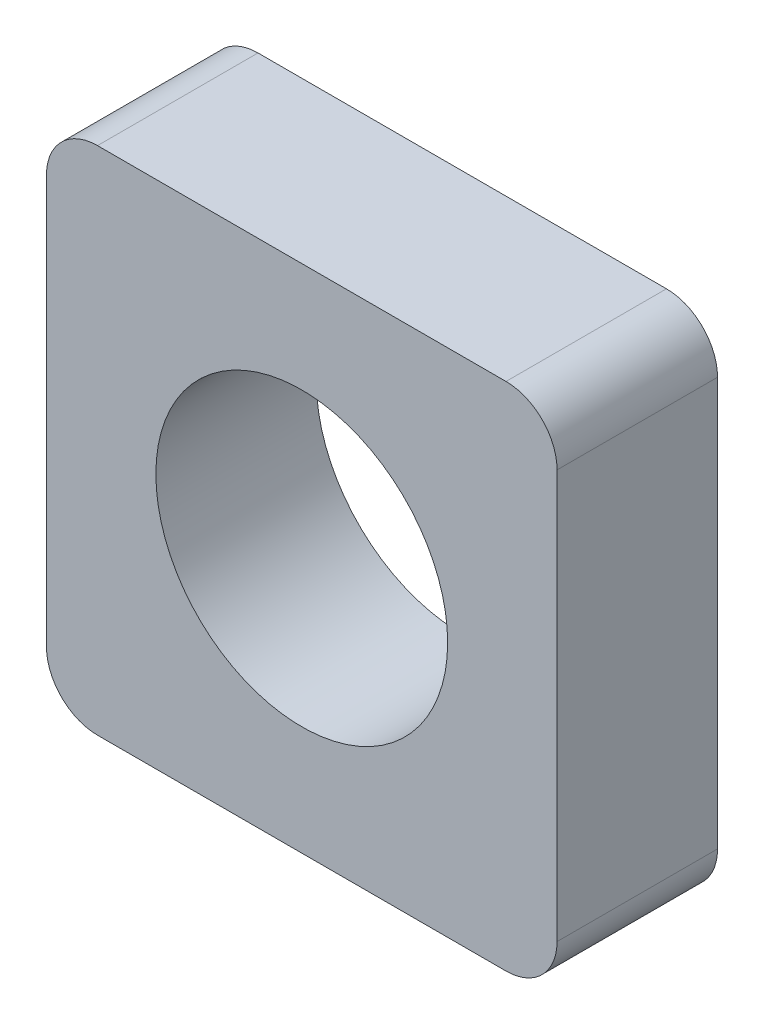
SolidWorks part; units mm, degrees
material "Cast Stainless Steel"
ref_plane "Front Plane" through (0, 0, 0) normal (0, 0, 1) x (1, 0, 0)
ref_plane "Top Plane" through (0, 0, 0) normal (0, 1, 0) x (1, 0, 0)
ref_plane "Right Plane" through (0, 0, 0) normal (1, 0, 0) x (0, 0, -1)
sketch "Sketch1" plane through (0, 0, 0) normal (0, 0, 1) x (1, 0, 0)
  line L1 (-3.5, 3.5) -> (3.5, 3.5)
  line L2 (-3.5, 3.5) -> (-3.5, -3.5)
  line L3 (-3.5, -3.5) -> (3.5, -3.5)
  line L4 (3.5, 3.5) -> (3.5, -3.5)
  line L5 (-3.5, 3.5) -> (3.5, -3.5) construction
  line L6 (-3.5, -3.5) -> (3.5, 3.5) construction
  circle A0 centre (0, 0) radius 2
  dimension "D2" = 4
  dimension "D1" = 7
extrude "Boss-Extrude1" add sketch "Sketch1" along normal blind 2.2
fillet "Fillet1" radius 0.7 4 edges at (-3.5, -3.5, 1.1) (3.5, -3.5, 1.1) (-3.5, 3.5, 1.1) (3.5, 3.5, 1.1)
equation "\"d\"= 4"
equation "\"m\"= 2.2"
equation "\"S\"= 7"
equation "\"D1@Sketch1\"=\"S\""
equation "\"D2@Sketch1\"=\"d\""
equation "\"D1@Boss-Extrude1\"=\"m\""
equation "\"D1@Fillet1\"=\"S\"/10"
